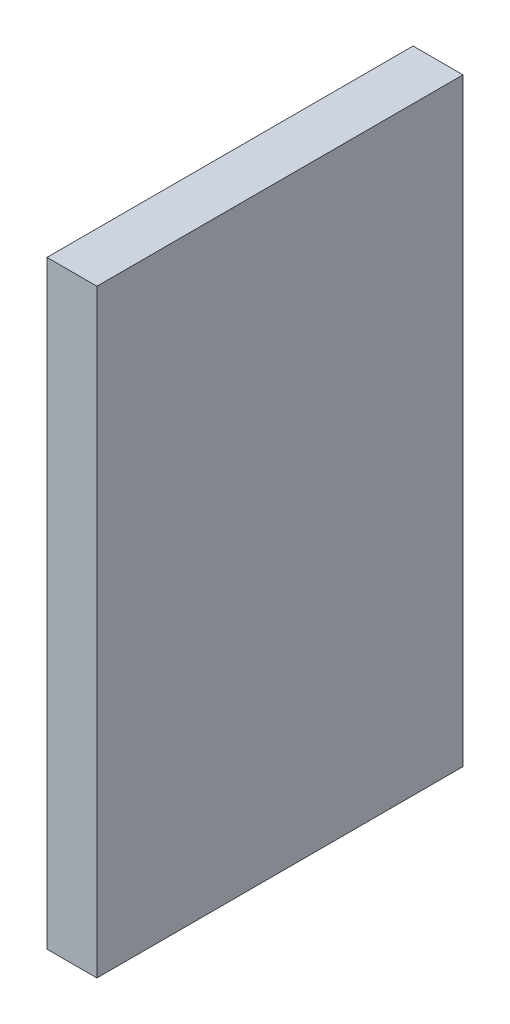
SolidWorks part; units mm, degrees
material "1.0553 (S355J0)"
ref_plane "Front Plane" through (0, 0, 0) normal (0, 0, 1) x (1, 0, 0)
ref_plane "Top Plane" through (0, 0, 0) normal (0, 1, 0) x (1, 0, 0)
ref_plane "Right Plane" through (0, 0, 0) normal (1, 0, 0) x (0, 0, -1)
sketch "Sketch1" plane through (0, 0, 0) normal (0, 1, 0) x (1, 0, 0)
  line L1 (37.5, 0) -> (-37.5, 0)
  line L2 (37.5, 0) -> (37.5, -550)
  line L3 (37.5, -550) -> (-37.5, -550)
  line L4 (-37.5, 0) -> (-37.5, -550)
  dimension "D1" = 75
  dimension "D2" = 550
extrude "Boss-Extrude1" add sketch "Sketch1" against normal blind 900
